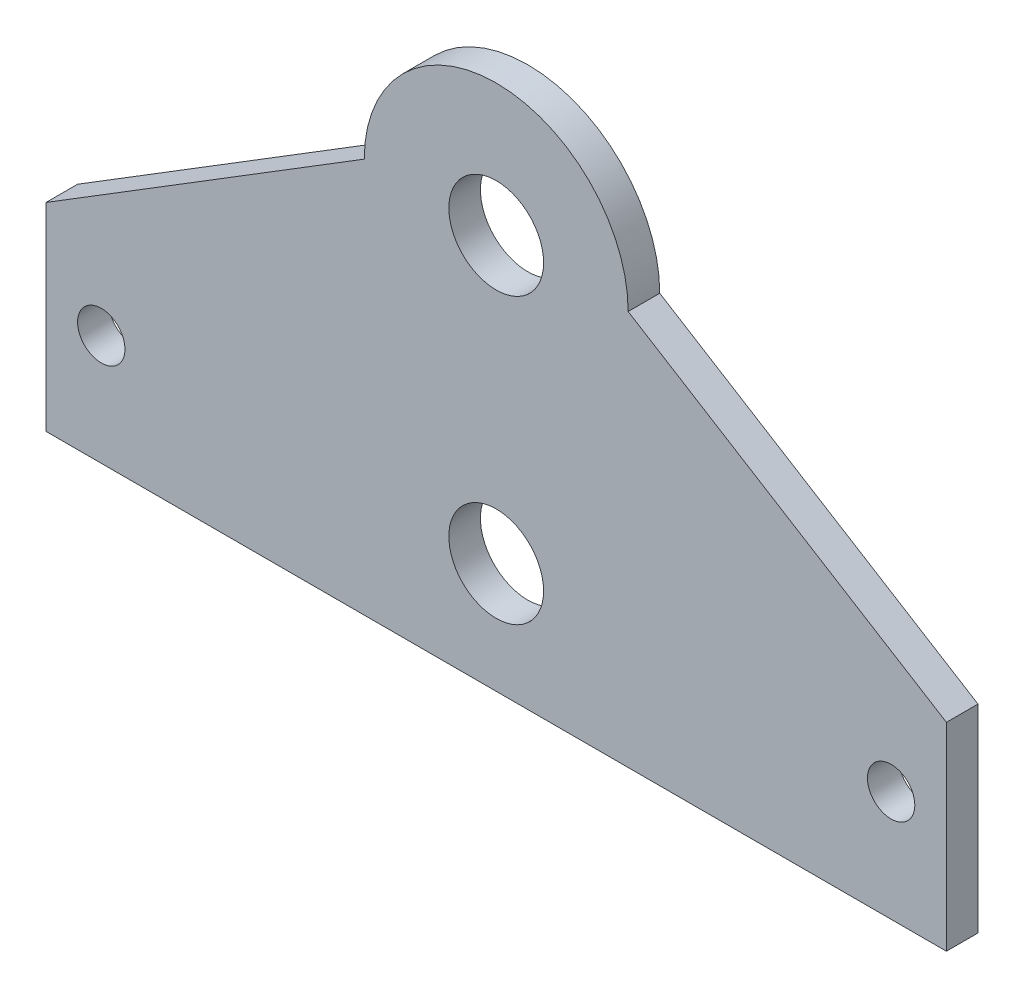
SolidWorks part; units mm, degrees
ref_plane "前视基准面" through (0, 0, 0) normal (0, 0, 1) x (1, 0, 0)
ref_plane "上视基准面" through (0, 0, 0) normal (0, 1, 0) x (1, 0, 0)
ref_plane "右视基准面" through (0, 0, 0) normal (1, 0, 0) x (0, 0, -1)
sketch "草图1" plane through (0, 0, 0) normal (0, 0, 1) x (1, 0, 0)
  line L323 (23.5948, -43.8726) -> (43.7411, -56.3205)
  line L336 (15.2411, -61.8726) -> (40.2411, -61.8726) construction
  line L337 (15.2411, -61.8726) -> (15.2411, -43.8726) construction
  line L338 (15.2411, -68.8726) -> (43.7411, -68.8726)
  line L340 (15.2411, -68.8726) -> (-13.2589, -68.8726)
  line L342 (43.7411, -56.3205) -> (43.7411, -68.8726)
  line L343 (6.8875, -43.8726) -> (-13.2589, -56.3205)
  line L344 (-13.2589, -56.3205) -> (-13.2589, -68.8726)
  circle A0 centre (15.2411, -61.8726) radius 3
  circle A1 centre (40.2411, -61.8726) radius 1.5
  circle A2 centre (-9.7589, -61.8726) radius 1.5
  circle A3 centre (15.2411, -43.8726) radius 3
  arc A4 (23.5948, -43.8726) -> (6.8875, -43.8726) centre (15.2411, -43.8726) ccw
extrude "凸台-拉伸1" add sketch "草图1" along normal blind 2
sketch "草图2" plane through (0, 0, 0) normal (0, 0, -1) x (-1, 0, 0)
  line L0 (-15.2411, -61.8726) -> (-15.2411, -68.8726)
  line L1 (13.2589, -68.8726) -> (-43.7411, -68.8726) construction
  line L2 (-15.2411, -68.8726) -> (-0.2411, -68.8726)
  line L3 (-0.2411, -68.8726) -> (-0.2411, -53.8726)
